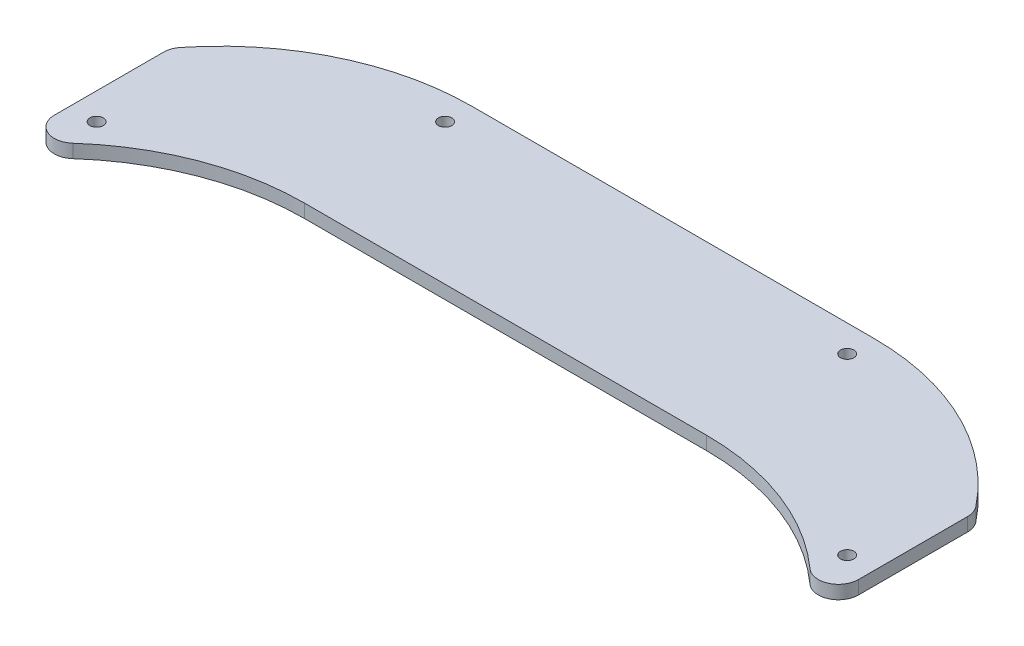
SolidWorks part; units mm, degrees
ref_plane "Front Plane" through (0, 0, 0) normal (0, 0, 1) x (1, 0, 0)
ref_plane "Top Plane" through (0, 0, 0) normal (0, 1, 0) x (1, 0, 0)
ref_plane "Right Plane" through (0, 0, 0) normal (1, 0, 0) x (0, 0, -1)
sketch "Sketch1" plane through (0, 0, 0) normal (0, 1, 0) x (1, 0, 0)
  line L0 (0, 40) -> (0, 0) construction
  line L1 (0, 0) -> (60, 0) construction
  line L2 (-30, 40) -> (30, 40)
  line L3 (60, 25) -> (60, 0)
  line L4 (30, 15) -> (-30, 15)
  line L5 (30, 15) -> (30, 40) construction
  line L6 (-60, 25) -> (-60, 0)
  arc A0 (30, 40) -> (60, 25) centre (30, 2.5) cw
  arc A1 (60, 0) -> (30, 15) centre (30, -22.5) ccw
  arc A2 (-60, 0) -> (-30, 15) centre (-30, -22.5) cw
  arc A3 (-30, 40) -> (-60, 25) centre (-30, 2.5) ccw
  point P9 (0, 15)
  dimension "D1" = 60
  dimension "D2" = 30
  dimension "D3" = 40
  dimension "D4" = 15
  dimension "D5" = 25
extrude "Boss-Extrude1" add sketch "Sketch1" along normal blind 2
sketch "Sketch2" plane through (0, 2, 0) normal (0, 1, 0) x (1, 0, 0)
  line L0 (60, 0) -> (60, 25) construction
  line L1 (30, 15) -> (60, 15) construction
  line L2 (30, 40) -> (30, 15) construction
  line L3 (0, 40) -> (0, 0) construction
  line L4 (30, 40) -> (-30, 40) construction
  circle A1 centre (56, 10) radius 1
  circle A2 centre (30, 36) radius 1
  circle A3 centre (-56, 10) radius 1
  circle A4 centre (-30, 36) radius 1
  dimension "D1" = 2
  dimension "D2" = 4
  dimension "D3" = 5
  dimension "D4" = 4
extrude "Cut-Extrude1" cut sketch "Sketch2" against normal blind 3
fillet "Fillet2" radius 3 4 edges at (-60, 1, -25) (60, 1, -25) (60, 1, 0) (-60, 1, 0)
